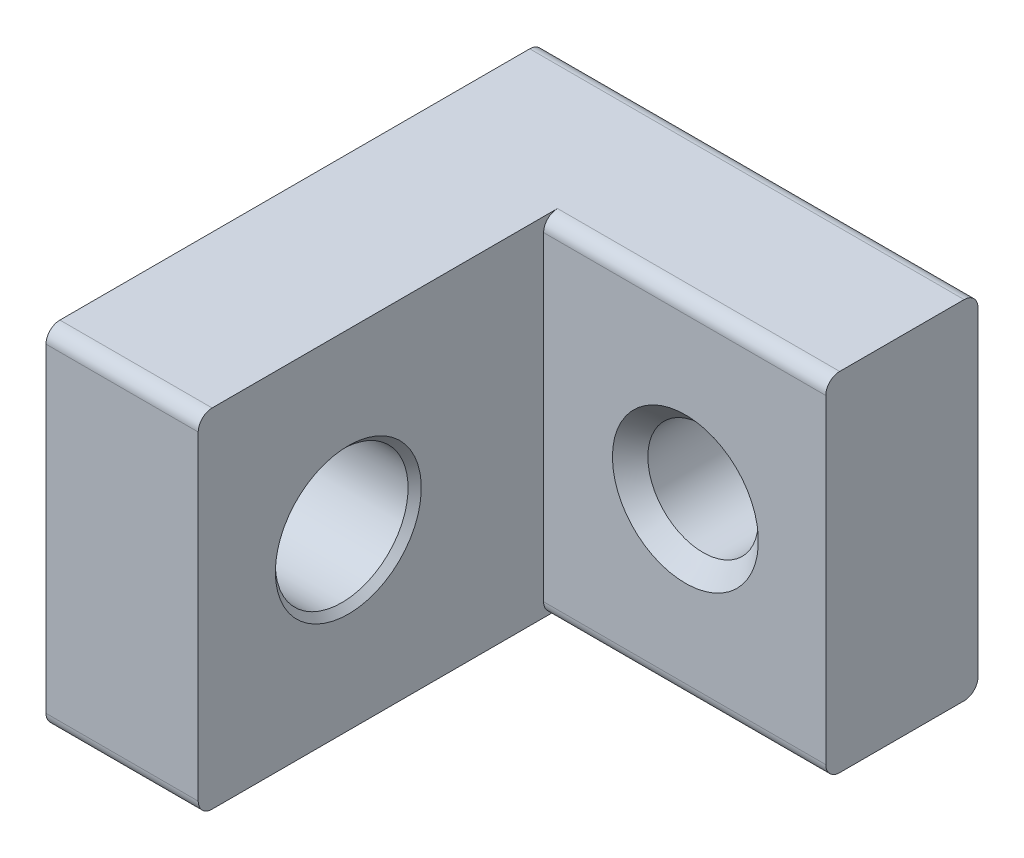
SolidWorks part; units mm, degrees
ref_plane "PL-01 Front" through (0, 0, 0) normal (0, 0, 1) x (1, 0, 0)
ref_plane "PL-02 Top" through (0, 0, 0) normal (0, 1, 0) x (1, 0, 0)
ref_plane "PL-03 Right" through (0, 0, 0) normal (1, 0, 0) x (0, 0, -1)
sketch "Sketch1" plane through (0, 0, 0) normal (0, 1, 0) x (1, 0, 0)
  line L0 (5.9436, -18.1864) -> (5.9436, -5.5626)
  line L1 (0.381, 0) -> (16.256, 0)
  line L2 (0.381, 0) -> (0.381, -18.1864)
  line L3 (0.381, -18.1864) -> (5.9436, -18.1864)
  line L4 (16.256, 0) -> (16.256, -5.5626)
  line L5 (5.9436, -5.5626) -> (16.256, -5.5626)
  circle A0 centre (7.1662, -6.8619) radius 11.1125 construction
  dimension "D6" = 22.225
  dimension "D1" = 0.381
  dimension "D2" = 15.875
  dimension "D3" = 18.1864
  dimension "D4" = 5.5626
  dimension "D5" = 5.5626
extrude "Extrude1" add sketch "Sketch1" along normal mid plane 12.7
hole_wizard "#11 (0.191) Diameter Hole1" positions "Sketch3" profile "Sketch2" hole size "#11" standard "Ansi Inch" end condition up to next
sketch "Sketch3" plane through (0.381, 0, 0) normal (-1, 0, 0) x (0, 0, 1)
  point P0 (12.7, 0)
  dimension "D1" = 12.7
sketch "Sketch2" plane through (0.381, 0, 12.7) normal (0, 1, 0) x (0, 0, 1)
  line L0 (0, 0) -> (0, 5.5626)
  line L1 (0, 5.5626) -> (2.667, 5.5626)
  line L2 (2.4257, 5.3213) -> (2.4257, 0.2413)
  line L3 (2.4257, 0.2413) -> (2.667, 0)
  line L5 (2.667, 0) -> (0, 0)
  line L6 (-2.4257, 0.2413) -> (-2.667, 0) construction
  line L7 (2.667, 5.5626) -> (2.4257, 5.3213)
  line L8 (-2.667, 5.5626) -> (-2.4257, 5.3213) construction
  line L11 (0, -6.35) -> (0, 107.95) construction
  dimension "Thru Hole Dia." = 4.8514
  dimension "Thru Hole Depth" = 5.5626
  dimension "Near C'Sink Dia." = 5.334
  dimension "Near C'Sink Angle" = 90
  dimension "Far C'Sink Dia." = 5.334
  dimension "Far C'Sink Angle" = 90
hole_wizard "#10-32 Tapped Hole1" positions "Sketch5" profile "Sketch4" tap size "#10-32" standard "Ansi Inch" end condition up to next
sketch "Sketch5" plane through (0, 0, 0) normal (0, 0, -1) x (-1, 0, 0)
  point P0 (-11.1252, 0)
  dimension "D1" = 10.7442
sketch "Sketch4" plane through (11.1252, 0, 0) normal (1, 0, 0) x (0, 1, 0)
  line L0 (0, 0) -> (0, 5.5626)
  line L1 (0, 5.5626) -> (2.667, 5.5626)
  line L2 (2.0193, 4.9149) -> (2.0193, 0.6477)
  line L3 (2.0193, 0.6477) -> (2.667, 0)
  line L5 (2.667, 0) -> (0, 0)
  line L6 (-2.0193, 0.6477) -> (-2.667, 0) construction
  line L7 (2.667, 5.5626) -> (2.0193, 4.9149)
  line L8 (-2.667, 5.5626) -> (-2.0193, 4.9149) construction
  line L11 (0, -6.35) -> (0, 107.95) construction
  dimension "Thread Major Dia." = 4.0386
  dimension "Thru Tap Drill Depth" = 5.5626
  dimension "Near C'Sink Dia." = 5.334
  dimension "Near C'Sink Angle" = 90
  dimension "Far C'Sink Dia." = 5.334
  dimension "Far C'Sink Angle" = 90
fillet "Fillet1" radius 0.508 6 edges at (8.3185, -6.35, 0) (11.0998, -6.35, 5.5626) (3.1623, -6.35, 18.1864) (3.1623, 6.35, 18.1864) (11.0998, 6.35, 5.5626) (8.3185, 6.35, 0)
pattern_linear "LPattern1" [suppressed] count 6 spacing 22.606
